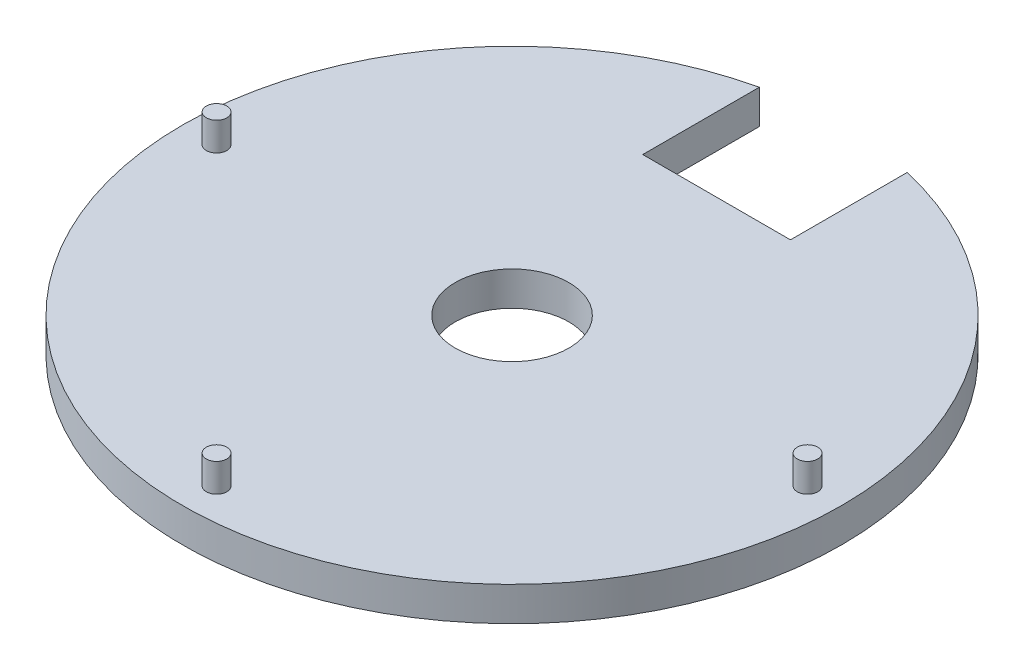
SolidWorks part; units mm, degrees
ref_plane "Front Plane" through (0, 0, 0) normal (0, 0, 1) x (1, 0, 0)
ref_plane "Top Plane" through (0, 0, 0) normal (0, 1, 0) x (1, 0, 0)
ref_plane "Right Plane" through (0, 0, 0) normal (1, 0, 0) x (0, 0, -1)
sketch "Sketch1" plane through (0, 0, 0) normal (0, 1, 0) x (1, 0, 0)
  circle A0 centre (0, 0) radius 29
extrude "Boss-Extrude1" add sketch "Sketch1" along normal blind 3 contours A0
sketch "Sketch2" plane through (0, 3, 0) normal (0, 1, 0) x (1, 0, 0)
  line L1 (0, 29) -> (6.5, 29)
  line L2 (6.5, 29) -> (6.5, 18)
  line L3 (6.5, 18) -> (-6.5, 18)
  line L4 (-6.5, 18) -> (-6.5, 29)
  line L5 (-6.5, 29) -> (0, 29)
  circle A0 centre (0, 0) radius 29 construction
extrude "Cut-Extrude1" cut sketch "Sketch2" against normal blind 3 contours L1 L2 L3 L4 L5
sketch "Sketch6" plane through (0, 3, 0) normal (0, 1, 0) x (1, 0, 0)
  line L0 (0, 0) -> (26, 0)
  line L1 (0, 0) -> (-26, 0)
  line L2 (0, 0) -> (0, -26)
  circle A0 centre (-26, 0) radius 0.9
  circle A1 centre (26, 0) radius 0.9
  circle A2 centre (0, -26) radius 0.9
extrude "Boss-Extrude3" add sketch "Sketch6" along normal blind 2.5 contours A0 | A1
sketch "Sketch7" plane through (0, 3, 0) normal (0, 1, 0) x (1, 0, 0)
  circle A0 centre (0, -26) radius 0.9
extrude "Boss-Extrude4" add sketch "Sketch7" along normal blind 2.5
sketch "Sketch8" plane through (0, 3, 0) normal (0, 1, 0) x (1, 0, 0)
  circle A0 centre (0, 0) radius 5
extrude "Cut-Extrude2" cut sketch "Sketch8" against normal blind 3
